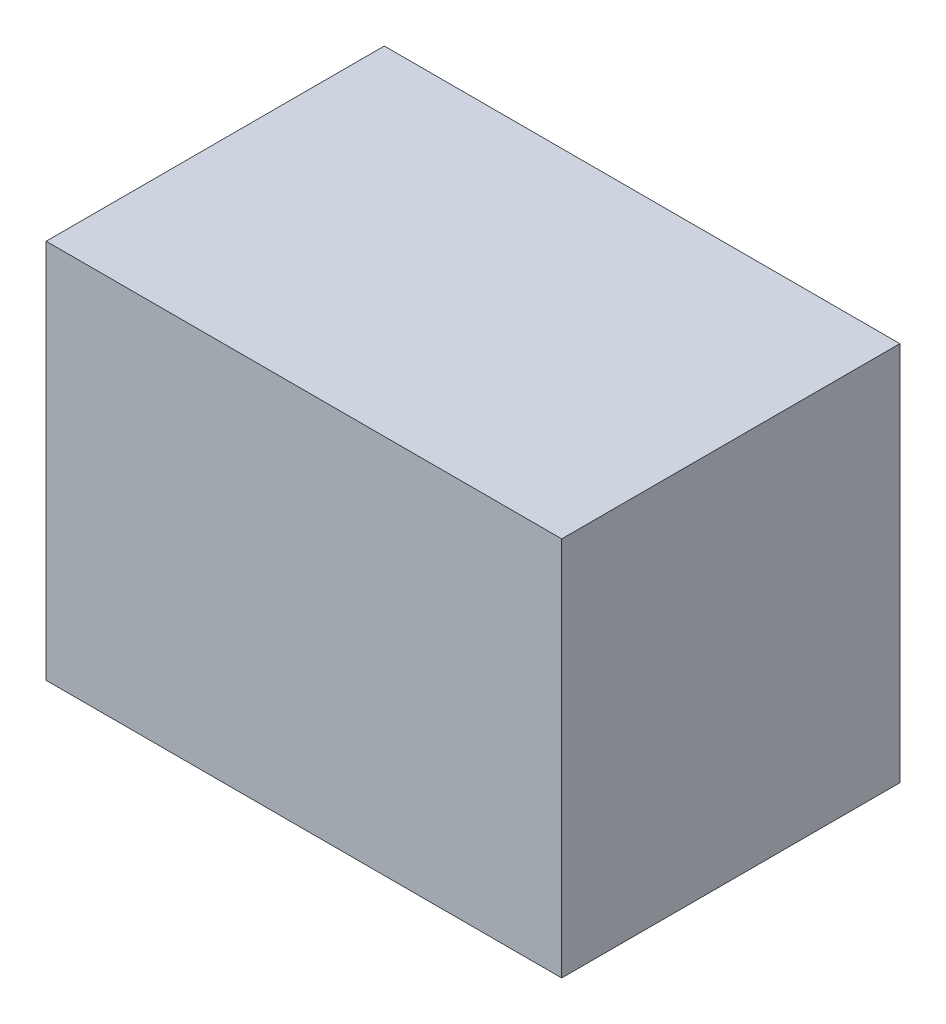
SolidWorks part; units mm, degrees
material "201 Annealed Stainless Steel (SS)"
ref_plane "Front Plane" through (0, 0, 0) normal (0, 0, 1) x (1, 0, 0)
ref_plane "Top Plane" through (0, 0, 0) normal (0, 1, 0) x (1, 0, 0)
ref_plane "Right Plane" through (0, 0, 0) normal (1, 0, 0) x (0, 0, -1)
sketch "Sketch1" plane through (0, 0, 0) normal (0, 0, 1) x (1, 0, 0)
  line L1 (0, 0) -> (16.4592, 0)
  line L2 (0, 0) -> (0, 12.1412)
  line L3 (0, 12.1412) -> (16.4592, 12.1412)
  line L4 (16.4592, 0) -> (16.4592, 12.1412)
  dimension "D1" = 12.1412
  dimension "D2" = 16.4592
extrude "Boss-Extrude1" add sketch "Sketch1" along normal blind 10.795
sketch "Sketch2" plane through (0, 0, 0) normal (-1, 0, 0) x (0, 0, 1)
  line L0 (0, 6.0706) -> (10.795, 6.0706) construction
  line L1 (0, 12.1412) -> (0, 0) construction
  line L2 (10.795, 12.1412) -> (10.795, 0) construction
  line L3 (5.3975, 12.1412) -> (5.3975, 0) construction
  line L4 (10.795, 12.1412) -> (0, 12.1412) construction
  line L5 (10.795, 0) -> (0, 0) construction
  line L6 (1.524, 1.778) -> (1.524, 10.3632)
  line L7 (1.524, 10.3632) -> (7.9458, 10.3632)
  line L8 (7.9458, 10.3632) -> (9.652, 8.657)
  line L9 (9.652, 8.657) -> (9.652, 3.4842)
  line L10 (9.652, 3.4842) -> (7.9458, 1.778)
  line L11 (7.9458, 1.778) -> (1.524, 1.778)
  line L13 (3.937, 3.3401) -> (6.9342, 3.3401)
  line L14 (3.937, 3.3401) -> (3.937, 8.8011)
  line L15 (3.937, 8.8011) -> (6.9342, 8.8011)
  line L16 (6.9342, 3.3401) -> (6.9342, 8.8011)
  line L17 (3.937, 3.3401) -> (6.9342, 8.8011) construction
  line L18 (3.937, 8.8011) -> (6.9342, 3.3401) construction
  point P16 (5.4356, 6.0706)
  dimension "D1" = 1.524
  dimension "D2" = 1.778
  dimension "D3" = 1.143
  dimension "D4" = 2.413
  dimension "D5" = 5.461
  dimension "D6" = 2.9972
  dimension "D7" = 2.413
extrude "Cut-Extrude1" cut sketch "Sketch2" against normal blind 9.017
